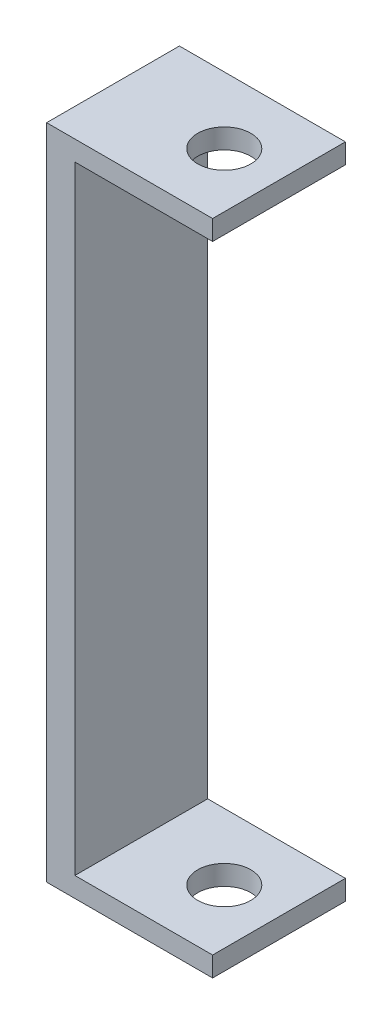
SolidWorks part; units mm, degrees
ref_plane "Front Plane" through (0, 0, 0) normal (0, 0, 1) x (1, 0, 0)
ref_plane "Top Plane" through (0, 0, 0) normal (0, 1, 0) x (1, 0, 0)
ref_plane "Right Plane" through (0, 0, 0) normal (1, 0, 0) x (0, 0, -1)
sketch "Sketch1" plane through (0, 0, 0) normal (0, 1, 0) x (1, 0, 0)
  line L0 (28.7683, 10) -> (-2.2222, 10) construction
  line L1 (0, 0) -> (25, 0)
  line L2 (0, 0) -> (0, 20)
  line L3 (0, 20) -> (25, 20)
  line L4 (25, 0) -> (25, 20)
  circle A0 centre (16.7601, 10) radius 4
  dimension "D3" = 8
  dimension "D1" = 20
  dimension "D2" = 25
extrude "Boss-Extrude1" add sketch "Sketch1" along normal blind 3
sketch "Sketch2" plane through (0, 3, 0) normal (0, 1, 0) x (1, 0, 0)
  line L0 (25, 0) -> (25, 20) construction
  line L1 (4.2601, 20) -> (4.2601, 0)
  line L2 (25, 20) -> (0, 20) construction
  line L3 (0, 0) -> (25, 0) construction
  line L4 (4.2601, 20) -> (0, 20)
  line L5 (0, 20) -> (0, 0)
  line L6 (0, 0) -> (4.2601, 0)
  circle A0 centre (16.7601, 10) radius 4 construction
  dimension "D1" = 8.2399
  dimension "D2" = 12.5
extrude "Boss-Extrude2" add sketch "Sketch2" along normal blind 93.06
sketch "Sketch3" plane through (0, 96.06, 0) normal (0, 1, 0) x (1, 0, 0)
  line L1 (0, 20) -> (25, 20)
  line L2 (0, 20) -> (0, 0)
  line L3 (0, 0) -> (25, 0)
  line L4 (25, 20) -> (25, 0)
  circle A0 centre (16.7601, 10) radius 4
extrude "Boss-Extrude3" add sketch "Sketch3" along normal blind 3
